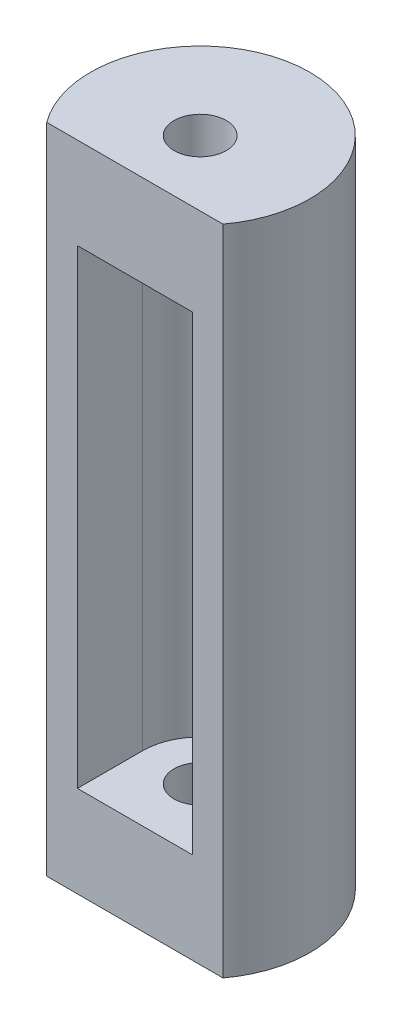
SolidWorks part; units mm, degrees
ref_plane "Front Plane" through (0, 0, 0) normal (0, 0, 1) x (1, 0, 0)
ref_plane "Top Plane" through (0, 0, 0) normal (0, 1, 0) x (1, 0, 0)
ref_plane "Right Plane" through (0, 0, 0) normal (1, 0, 0) x (0, 0, -1)
sketch "Sketch1" plane through (0, 0, 0) normal (0, 1, 0) x (1, 0, 0)
  line L0 (6.7498, -5) -> (-6.7498, -5)
  arc A0 (6.7498, -5) -> (-6.7498, -5) centre (0, 0) ccw
  circle A1 centre (0, 0) radius 2
  dimension "D1" = 16.8
  dimension "D3" = 4
  dimension "D2" = 5
extrude "Boss-Extrude1" add sketch "Sketch1" along normal blind 7
sketch "Sketch3" plane through (0, 7, 0) normal (0, 1, 0) x (1, 0, 0)
  line L0 (-4.4, 0) -> (-4.4, -5)
  line L1 (-6.7498, -5) -> (6.7498, -5) construction
  line L2 (4.4, 0) -> (4.4, -5)
  line L3 (4.4, -5) -> (6.7498, -5)
  line L4 (-4.4, -5) -> (-6.7498, -5)
  arc A0 (4.4, 0) -> (-4.4, 0) centre (0, 0) ccw
  arc A1 (6.7498, -5) -> (-6.7498, -5) centre (0, 0) ccw
  arc A2 (6.7498, -5) -> (-6.7498, -5) centre (0, 0) ccw construction
  dimension "D1" = 8.8
extrude "Boss-Extrude3" add sketch "Sketch3" along normal blind 36
sketch "Sketch5" plane through (0, 43, 0) normal (0, 1, 0) x (1, 0, 0)
  line L0 (6.7498, -5) -> (-6.7498, -5)
  arc A0 (6.7498, -5) -> (-6.7498, -5) centre (0, 0) ccw
  arc A1 (6.7498, -5) -> (-6.7498, -5) centre (0, 0) ccw construction
  circle A2 centre (0, 0) radius 2
  circle A3 centre (0, 0) radius 2 construction
extrude "Boss-Extrude4" add sketch "Sketch5" along normal blind 7
